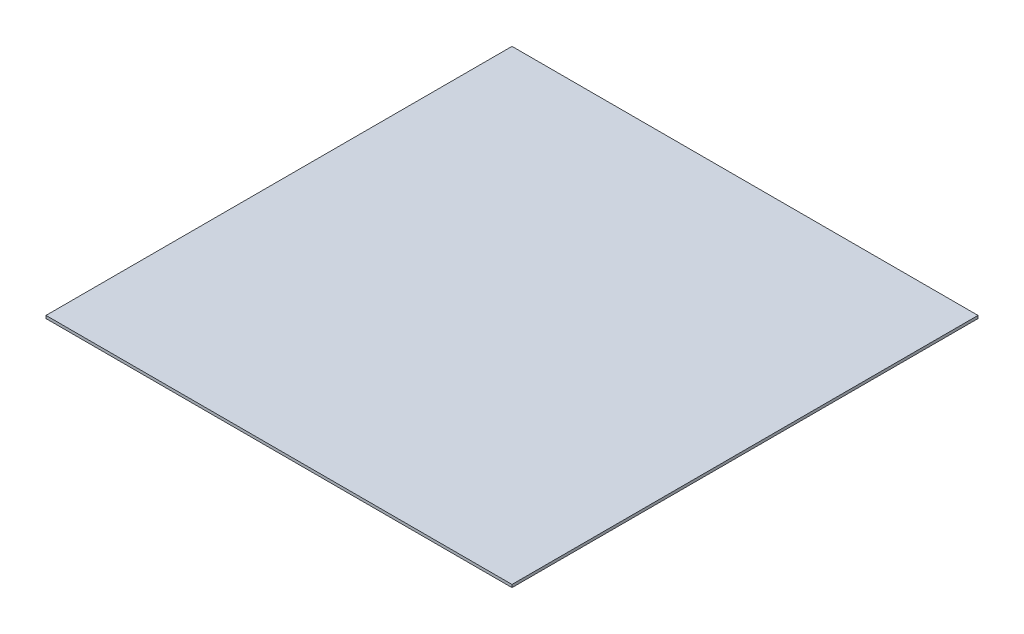
SolidWorks part; units mm, degrees
ref_plane "Front Plane" through (0, 0, 0) normal (0, 0, 1) x (1, 0, 0)
ref_plane "Top Plane" through (0, 0, 0) normal (0, 1, 0) x (1, 0, 0)
ref_plane "Right Plane" through (0, 0, 0) normal (1, 0, 0) x (0, 0, -1)
sketch "Sketch1" plane through (0, 0, 0) normal (0, 1, 0) x (1, 0, 0)
  line L1 (-150, 150) -> (150, 150)
  line L2 (-150, 150) -> (-150, -150)
  line L3 (-150, -150) -> (150, -150)
  line L4 (150, 150) -> (150, -150)
  line L5 (-150, 150) -> (150, -150) construction
  line L6 (-150, -150) -> (150, 150) construction
  point P0 (0, 0)
  dimension "D1" = 300
extrude "Boss-Extrude1" add sketch "Sketch1" along normal blind 1.8
